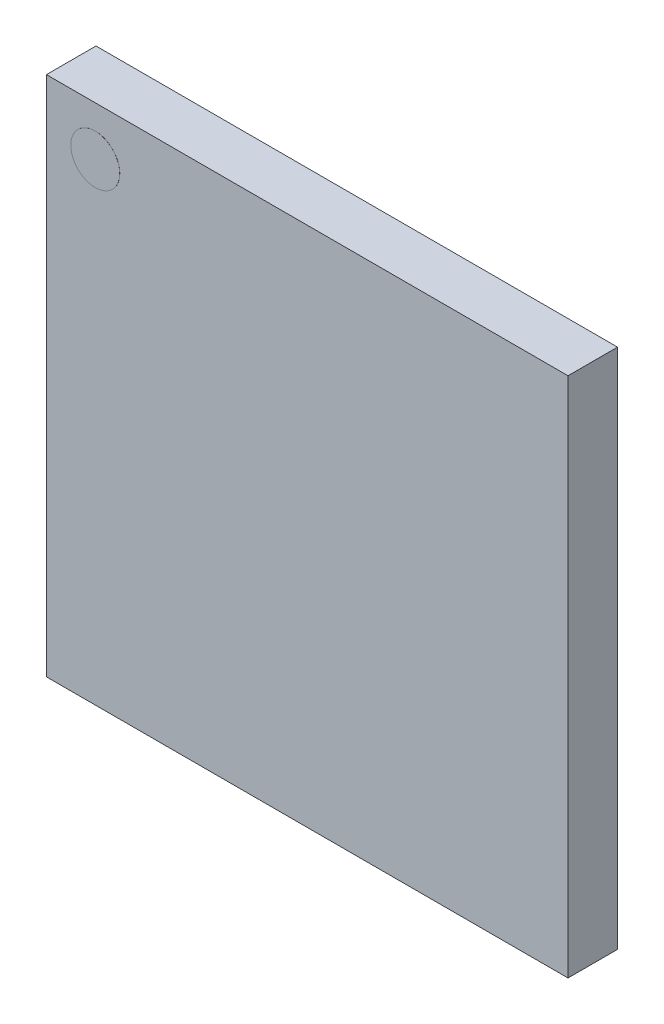
SolidWorks part; units mm, degrees
ref_plane "Plan de face" through (0, 0, 0) normal (0, 0, 1) x (1, 0, 0)
ref_plane "Plan de dessus" through (0, 0, 0) normal (0, 1, 0) x (1, 0, 0)
ref_plane "Plan de droite" through (0, 0, 0) normal (1, 0, 0) x (0, 0, -1)
sketch "Esquisse1" plane through (0, 0, 0) normal (0, 0, 1) x (1, 0, 0)
  line L1 (-4, 4) -> (4, 4)
  line L2 (-4, 4) -> (-4, -4)
  line L3 (-4, -4) -> (4, -4)
  line L4 (4, 4) -> (4, -4)
  line L5 (-4, 4) -> (4, -4) construction
  line L6 (-4, -4) -> (4, 4) construction
  point P0 (0, 0)
  dimension "D1" = 8
extrude "body" add sketch "Esquisse1" along normal blind 0.76 from offset 0.15
ref_plane "plan ball A1" through (0, 3.6, 0) normal (0, 1, 0) x (1, 0, 0)
sketch "Esquisse2" plane through (0, 3.6, 0) normal (0, 1, 0) x (1, 0, 0)
  line L0 (0.2377, 0) -> (-3.4146, 0) construction
  line L1 (-3.6, 0) -> (-3.6, -0.275)
  line L2 (-3.4146, 0) -> (-3.6, 0)
  line L3 (-3.6, 0) -> (-3.6, -0.15) construction
  line L4 (4, -0.15) -> (-4, -0.15) construction
  arc A0 (-3.6, -0.275) -> (-3.4146, 0) centre (-3.6, -0.075) ccw
  point P10 (-3.6, -0.075)
  dimension "D1" = 0.4
  dimension "D2" = 3.6
revolve "ball A1" add sketch "Esquisse2" angle 360 about L1
pattern_linear "ball array" count 10 spacing 0.8 along (1, 0, 0) count 10 spacing 0.8 along (0, -1, 0) of "ball A1"
sketch "Esquisse3" plane through (0, 0, 0.91) normal (0, 0, 1) x (1, 0, 0)
  line L0 (-4, 4) -> (-4, -4) construction
  line L1 (4, 4) -> (-4, 4) construction
  circle A0 centre (-3.25, 3.25) radius 0.375
  dimension "D1" = 0.75
  dimension "D2" = 0.75
  dimension "D3" = 0.75
extrude "A1 mark" add sketch "Esquisse3" along normal blind 0.001
